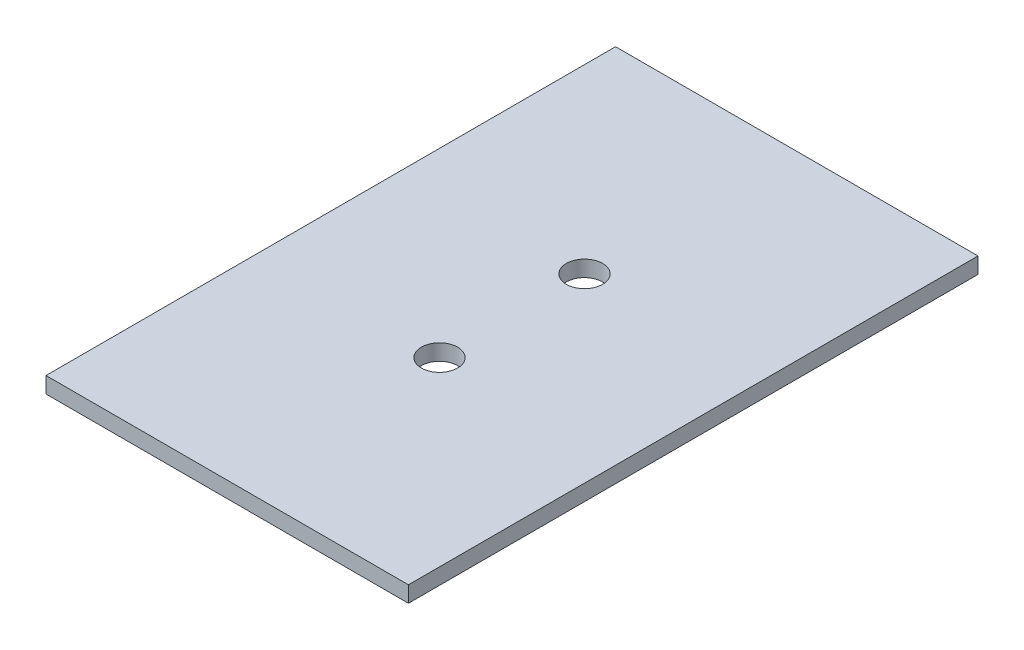
SolidWorks part; units mm, degrees
ref_plane "Front Plane" through (0, 0, 0) normal (0, 0, 1) x (1, 0, 0)
ref_plane "Top Plane" through (0, 0, 0) normal (0, 1, 0) x (1, 0, 0)
ref_plane "Right Plane" through (0, 0, 0) normal (1, 0, 0) x (0, 0, -1)
sketch "Sketch1" plane through (0, 0, 0) normal (0, 1, 0) x (1, 0, 0)
  line L1 (-17.5, 27.5) -> (17.5, 27.5)
  line L2 (-17.5, 27.5) -> (-17.5, -27.5)
  line L3 (-17.5, -27.5) -> (17.5, -27.5)
  line L4 (17.5, 27.5) -> (17.5, -27.5)
  point P4 (0, 27.5)
  point P6 (17.5, 0)
  dimension "D1" = 55
  dimension "D2" = 35
extrude "Boss-Extrude1" add sketch "Sketch1" along normal mid plane 1.55
sketch "Sketch2" plane through (0, 0, 0) normal (0, 1, 0) x (1, 0, 0)
  line L0 (0, 7) -> (0, -7) construction
  line L1 (3.4966, 0) -> (-3.4966, 0) construction
  circle A0 centre (0, 7) radius 1.75
  circle A1 centre (0, -7) radius 1.75
  point P5 (0, 0)
  dimension "D1" = 3.5
  dimension "D2" = 14
extrude "Cut-Extrude1" cut sketch "Sketch2" against normal mid plane 10
